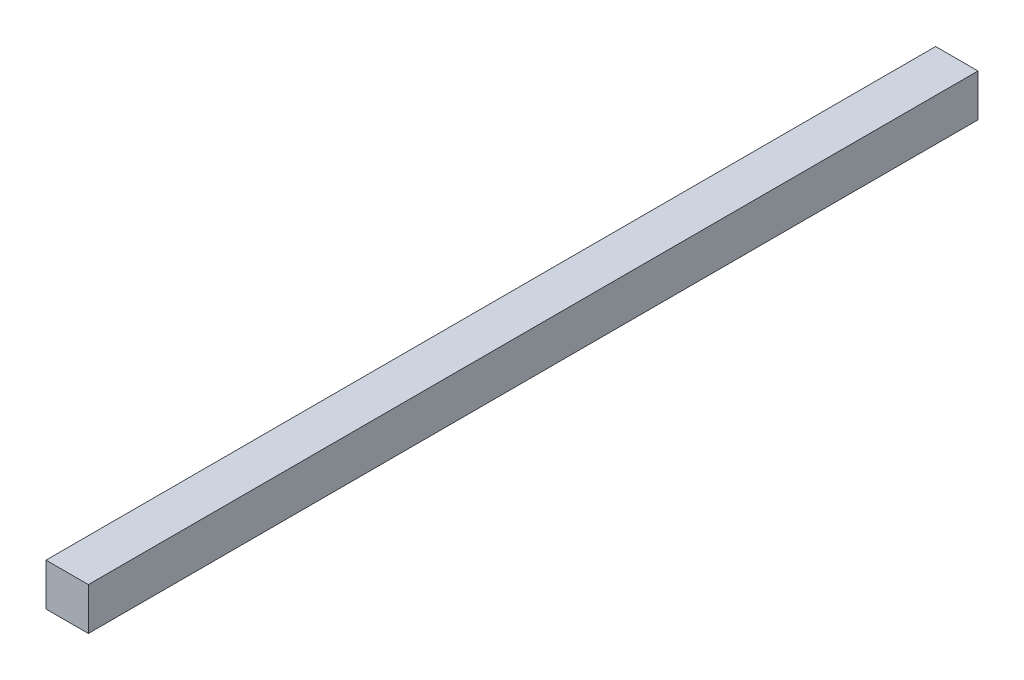
SolidWorks part; units mm, degrees
ref_plane "Front" through (0, 0, 0) normal (0, 0, 1) x (1, 0, 0)
ref_plane "Top" through (0, 0, 0) normal (0, 1, 0) x (1, 0, 0)
ref_plane "Right" through (0, 0, 0) normal (1, 0, 0) x (0, 0, -1)
sketch "Sketch1" plane through (0, 0, 0) normal (0, 0, 1) x (1, 0, 0)
  line L1 (0, 0) -> (-2.54, 0)
  line L2 (0, 0) -> (0, 2.54)
  line L3 (0, 2.54) -> (-2.54, 2.54)
  line L4 (-2.54, 0) -> (-2.54, 2.54)
  dimension "D1" = 2.54
extrude "Boss-Extrude1" add sketch "Sketch1" along normal blind 53.34
